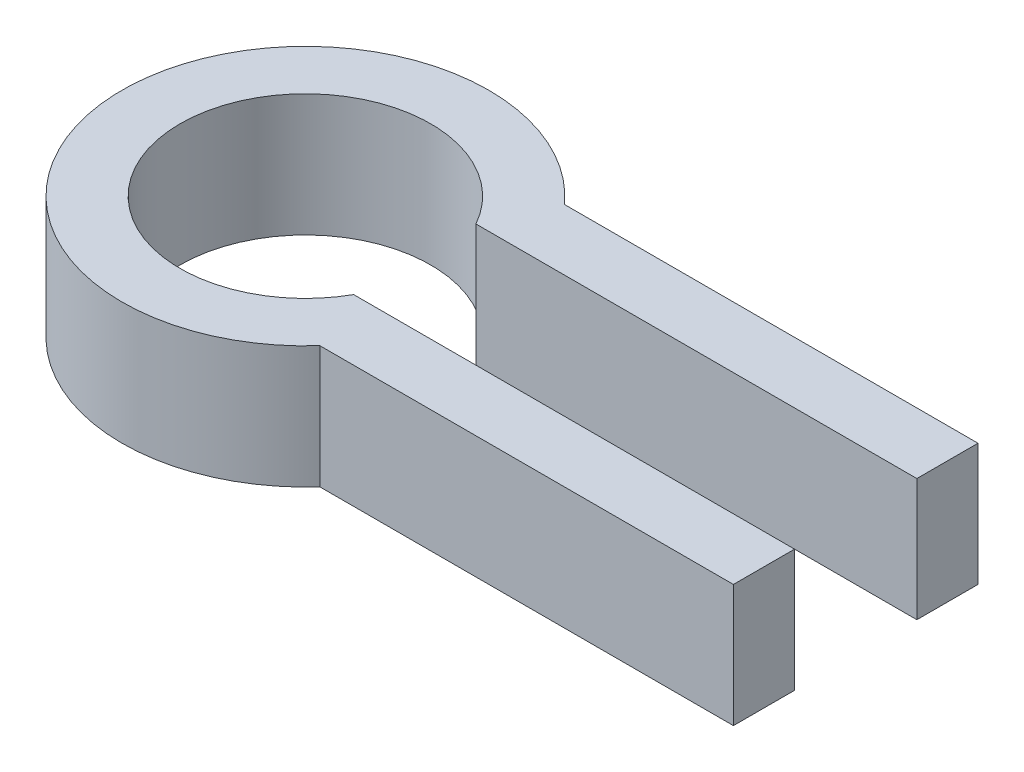
SolidWorks part; units mm, degrees
ref_plane "前视基准面" through (0, 0, 0) normal (0, 0, 1) x (1, 0, 0)
ref_plane "上视基准面" through (0, 0, 0) normal (0, 1, 0) x (1, 0, 0)
ref_plane "右视基准面" through (0, 0, 0) normal (1, 0, 0) x (0, 0, -1)
sketch "草图1" plane through (0, 0, 0) normal (0, 1, 0) x (1, 0, 0)
  line L0 (14.1421, 5) -> (50, 5)
  line L1 (-50, -5) -> (50, -5) construction
  line L2 (-50, -5) -> (-50, 5) construction
  line L3 (-50, 5) -> (50, 5) construction
  line L4 (50, -5) -> (50, 5) construction
  line L5 (-50, -5) -> (50, 5) construction
  line L6 (-50, 5) -> (50, -5) construction
  line L7 (14.1421, -5) -> (50, -5)
  line L8 (11.1803, 10) -> (55, 10)
  line L9 (55, -10) -> (55, 10)
  line L10 (11.1803, -10) -> (55, -10)
  line L11 (14.1421, 10) -> (55, 10) construction
  line L12 (14.1421, -10) -> (55, -10) construction
  line L13 (8.9478, 5) -> (14.1421, 5)
  line L14 (8.9478, -5) -> (14.1421, -5)
  line L15 (50, 5) -> (55, 5)
  line L16 (50, -5) -> (55, -5)
  circle A0 centre (0, 0) radius 10.25
  circle A1 centre (0, 0) radius 15
  point P8 (14.1421, 5)
  point P9 (14.1421, -5)
  point P18 (8.9478, 5)
  point P19 (8.9478, -5)
  dimension "D1" = 20.5
  dimension "D2" = 30
  dimension "D3" = 10
  dimension "D4" = 100
  dimension "D5" = 35.8579
  dimension "D6" = 35.8579
  dimension "D7" = 5
  dimension "D8" = 5.1944
  dimension "D9" = 5.1944
  dimension "D10" = 5
  dimension "D11" = 5
  dimension "D12" = 5
extrude "凸台-拉伸1" add sketch "草图1" along normal blind 10 contours A1 L0 L15 L9 L8 | A1 L14 A0 L13 | A1 L10 L9 L16 L7
sketch "草图2" plane through (55, 0, 0) normal (1, 0, 0) x (0, 0, -1)
  line L0 (5, 0) -> (10, 0) construction
  line L1 (10, 0) -> (10, 10) construction
  line L2 (10, 10) -> (5, 10) construction
  line L3 (5, 10) -> (5, 0) construction
  line L4 (-10, 0) -> (-5, 0) construction
  line L5 (-5, 0) -> (-5, 10) construction
  line L6 (-5, 10) -> (-10, 10) construction
  line L7 (-10, 10) -> (-10, 0) construction
  line L8 (5, 0) -> (10, 0)
  line L9 (10, 0) -> (10, 10)
  line L10 (10, 10) -> (5, 10)
  line L11 (5, 10) -> (5, 0)
  line L12 (-10, 0) -> (-5, 0)
  line L13 (-5, 0) -> (-5, 10)
  line L14 (-5, 10) -> (-10, 10)
  line L15 (-10, 10) -> (-10, 0)
extrude "切除-拉伸1" cut sketch "草图2" against normal blind 10
